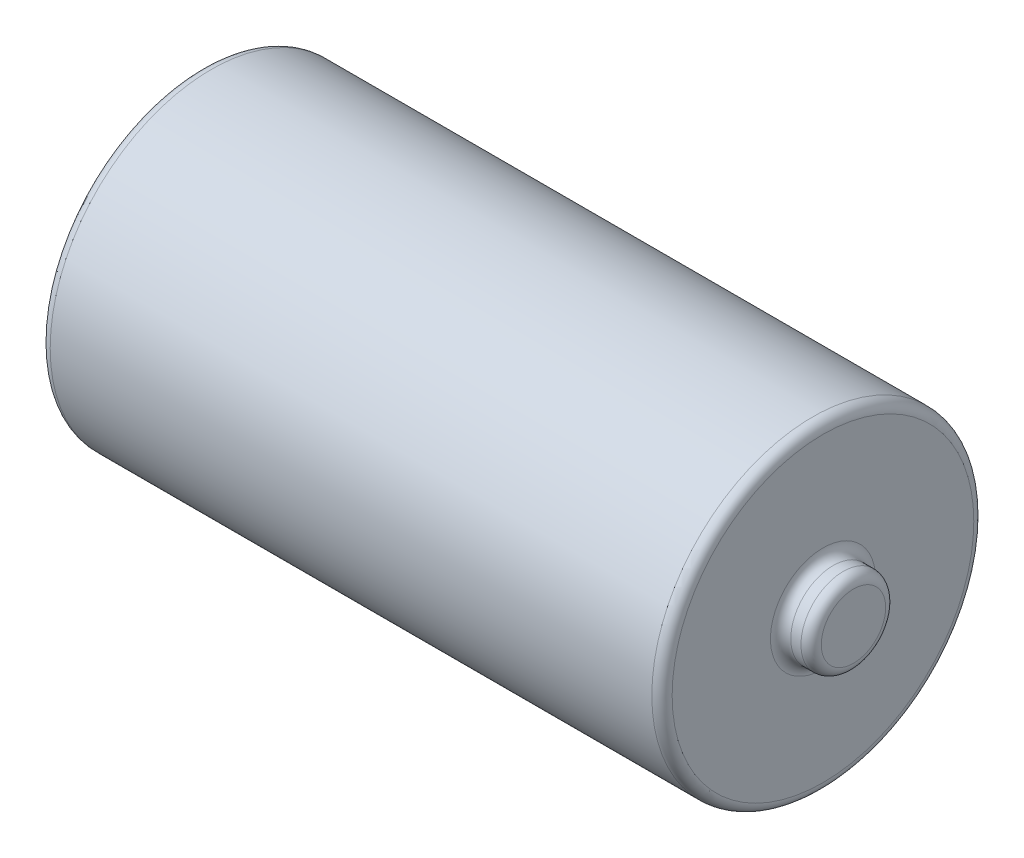
SolidWorks part; units mm, degrees
ref_plane "Front Plane" through (0, 0, 0) normal (0, 0, 1) x (1, 0, 0)
ref_plane "Top Plane" through (0, 0, 0) normal (0, 1, 0) x (1, 0, 0)
ref_plane "Right Plane" through (0, 0, 0) normal (1, 0, 0) x (0, 0, -1)
sketch "Sketch1" plane through (0, 0, 0) normal (1, 0, 0) x (0, 0, -1)
  circle A0 centre (0, 0) radius 12.065
  dimension "D1" = 24.13
extrude "Boss-Extrude1" add sketch "Sketch1" along normal mid plane 46.609
ref_axis "Axis1" through (23.3045, 0, 0) along (-1, 0, 0)
sketch "Sketch2" plane through (0, 0, 0) normal (0, 0, 1) x (1, 0, 0)
  line L0 (23.3045, 0) -> (-23.3045, 0) construction
  line L1 (23.3045, 0) -> (25.5905, 0)
  line L2 (23.3045, 0) -> (23.3045, 3.175)
  line L3 (23.3045, 3.175) -> (25.5905, 3.175)
  line L4 (25.5905, 0) -> (25.5905, 3.175)
  line L5 (23.3045, -12.065) -> (23.3045, 12.065) construction
  dimension "D1" = 3.175
  dimension "D2" = 2.286
revolve "Revolve1" add sketch "Sketch2" angle 360 about axis through (23.3045, 0, 0) along (-1, 0, 0)
fillet "Fillet2" radius 0.762 2 edges at (25.5905, 0, -3.175) (23.3045, 0, -3.175)
fillet "Fillet3" radius 0.762 2 edges at (23.3045, 0, -12.065) (-23.3045, 0, -12.065)
